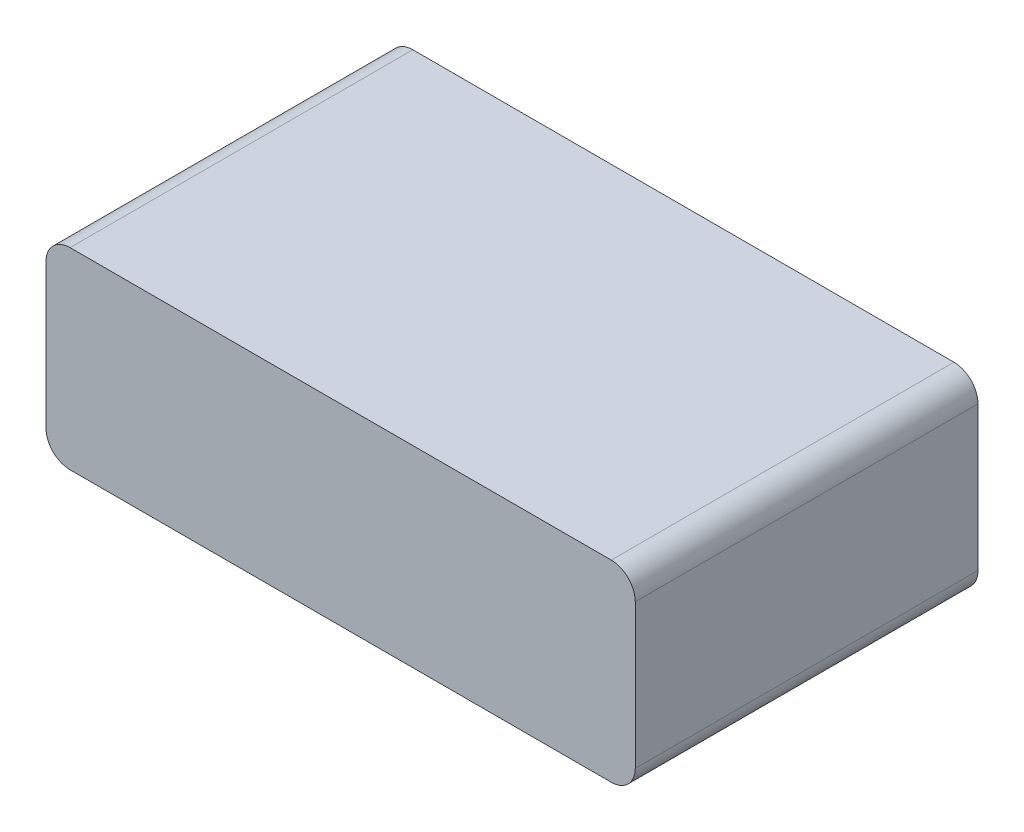
SolidWorks part; units mm, degrees
ref_plane "Front Plane" through (0, 0, 0) normal (0, 0, 1) x (1, 0, 0)
ref_plane "Top Plane" through (0, 0, 0) normal (0, 1, 0) x (1, 0, 0)
ref_plane "Right Plane" through (0, 0, 0) normal (1, 0, 0) x (0, 0, -1)
sketch "Sketch1" plane through (0, 0, 0) normal (0, 1, 0) x (1, 0, 0)
  line L1 (0, 0) -> (49, 0)
  line L2 (0, 0) -> (0, 28.5)
  line L3 (0, 28.5) -> (49, 28.5)
  line L4 (49, 0) -> (49, 28.5)
  dimension "D1" = 28.5
  dimension "D2" = 49
extrude "Boss-Extrude1" add sketch "Sketch1" along normal blind 16
fillet "Fillet1" radius 2 4 edges at (49, 0, -14.25) (49, 16, -14.25) (0, 0, -14.25) (0, 16, -14.25)
